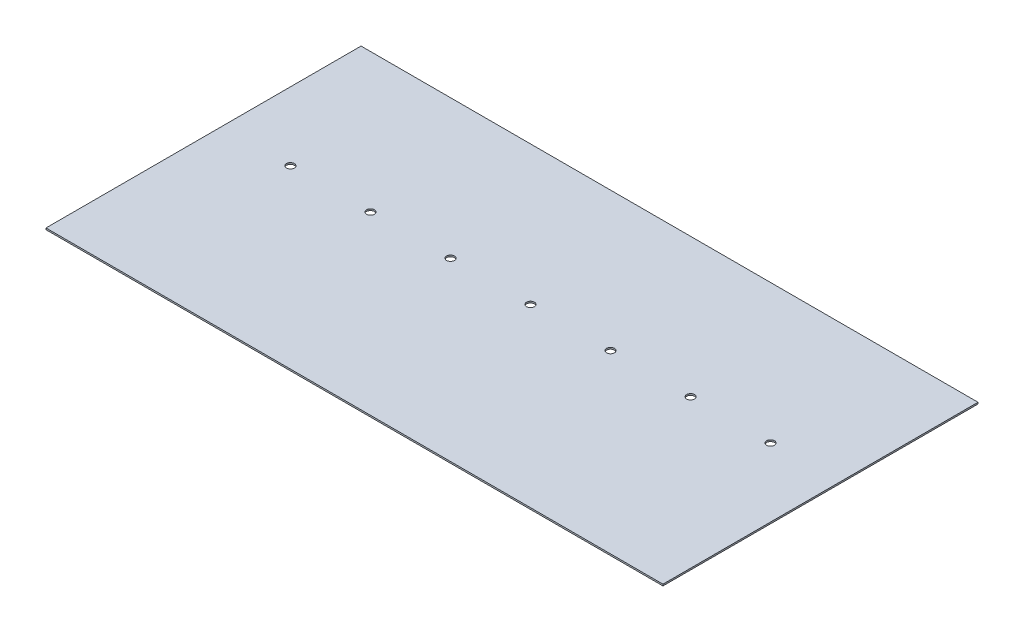
SolidWorks part; units mm, degrees
ref_plane "Front Plane" through (0, 0, 0) normal (0, 0, 1) x (1, 0, 0)
ref_plane "Top Plane" through (0, 0, 0) normal (0, 1, 0) x (1, 0, 0)
ref_plane "Right Plane" through (0, 0, 0) normal (1, 0, 0) x (0, 0, -1)
sketch "Sketch1" plane through (0, 0, 0) normal (0, 1, 0) x (1, 0, 0)
  line L0 (195.834, -199.9996) -> (195.834, -88.2396) construction
  line L1 (0, 0) -> (391.668, 0)
  line L2 (0, 0) -> (0, -199.9996)
  line L3 (0, -199.9996) -> (391.668, -199.9996)
  line L4 (391.668, 0) -> (391.668, -199.9996)
  line L5 (195.834, -88.2396) -> (391.668, -88.2396) construction
  line L6 (195.834, -88.2396) -> (0, -88.2396) construction
  circle A0 centre (195.834, -88.2396) radius 2.5
  circle A1 centre (145.034, -88.2396) radius 2.5
  circle A2 centre (94.234, -88.2396) radius 2.5
  circle A3 centre (43.434, -88.2396) radius 2.5
  circle A4 centre (195.834, -88.2396) radius 2.5
  circle A5 centre (145.034, -88.2396) radius 2.5
  circle A6 centre (94.234, -88.2396) radius 2.5
  circle A7 centre (246.634, -88.2396) radius 2.5
  circle A8 centre (195.834, -88.2396) radius 2.5
  circle A9 centre (145.034, -88.2396) radius 2.5
  circle A10 centre (297.434, -88.2396) radius 2.5
  circle A11 centre (246.634, -88.2396) radius 2.5
  circle A12 centre (195.834, -88.2396) radius 2.5
  circle A13 centre (246.634, -88.2396) radius 2.5
  circle A14 centre (297.434, -88.2396) radius 2.5
  circle A15 centre (348.234, -88.2396) radius 2.5
  dimension "D4" = 5
  dimension "D1" = 199.9996
  dimension "D2" = 391.668
  dimension "D3" = 111.76
  dimension "D5" = 4
  dimension "D6" = 4
extrude "Boss-Extrude1" add sketch "Sketch1" against normal blind 1 contours L4 L1 L2 L3 A15 A10 A7 A3 A2 A1 A0
